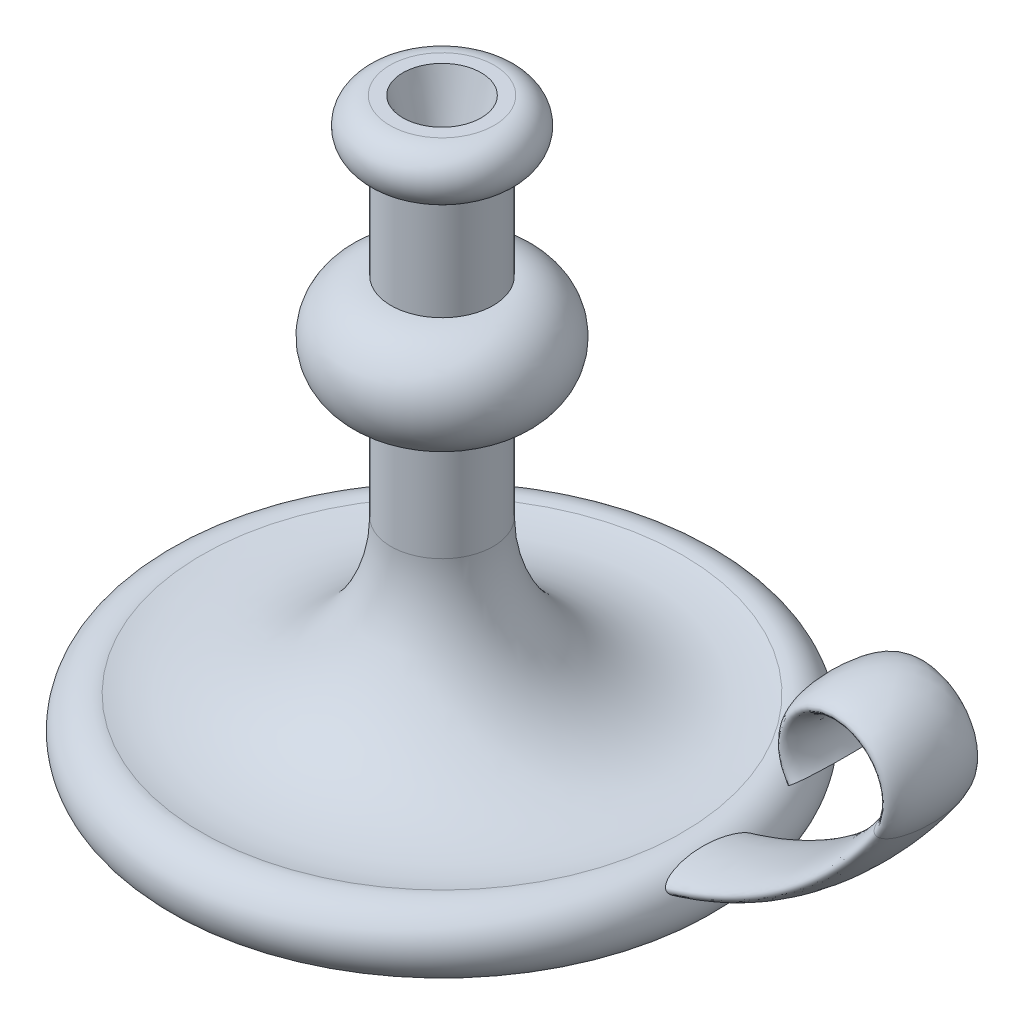
SolidWorks part; units mm, degrees
ref_plane "Front" through (0, 0, 0) normal (0, 0, 1) x (1, 0, 0)
ref_plane "Top" through (0, 0, 0) normal (0, 1, 0) x (1, 0, 0)
ref_plane "Right" through (0, 0, 0) normal (1, 0, 0) x (0, 0, -1)
sketch "草圖1" plane through (0, 0, 0) normal (0, 0, 1) x (1, 0, 0)
  line L0 (0, 0) -> (0, 220)
  line L1 (0, 220) -> (20, 220)
  line L2 (0, 0) -> (103.3169, 0)
  line L3 (19.5986, 200.0081) -> (19.5986, 160.0081)
  line L4 (19.5986, 120.0081) -> (19.5986, 80.0081)
  arc A0 (20, 220) -> (19.5986, 200.0081) centre (20, 210) cw
  arc A1 (19.5986, 160.0081) -> (19.5986, 120.0081) centre (19.5986, 140.0081) cw
  arc A2 (19.5986, 80.0081) -> (92.1449, 21.3345) centre (79.5986, 80.0081) ccw
  arc A3 (92.1449, 21.3345) -> (103.3169, 0) centre (94.7587, 9.1108) cw
  point P13 (0, 0)
  point P15 (0, 0)
  point P16 (0, 0)
  point P17 (0, 0)
  point P18 (0, 0)
  point P19 (0, 0)
  dimension "D4" = 10
  dimension "D5" = 20
  dimension "D7" = 60
  dimension "D8" = 12.5
  dimension "D1" = 220
  dimension "D2" = 20
  dimension "D3" = 103.3169
  dimension "D6" = 40
revolve "旋轉1" add sketch "草圖1" angle 360 about L0
sketch "草圖2" plane through (0, 0, 0) normal (0, 0, 1) x (1, 0, 0)
  line L0 (0, 10) -> (60, 10)
  line L1 (0, 227.4356) -> (0, 175.1288) construction
  line L2 (0, 200.0081) -> (0, 160.0081) construction
  line L3 (-103.3169, 0) -> (103.3169, 0) construction
  arc A0 (60, 10) -> (183.5921, 75) centre (60, 160) ccw
  arc A1 (183.5921, 75) -> (150.6342, 75) centre (167.1131, 86.3333) ccw
  dimension "D2" = 20
  dimension "D3" = 150
  dimension "D1" = 60
  dimension "D4" = 65
  dimension "D5" = 10
sketch "草圖3" plane through (0, 0, 0) normal (1, 0, 0) x (0, 0, -1)
  ellipse E0 centre (0, 10) end of major axis (17.5, 10) minor radius 5
  dimension "D1" = 35
  dimension "D2" = 10
sweep "掃出1" add profiles "草圖3" path "草圖2"
sketch "草圖5" plane through (0, 220, 0) normal (0, 1, 0) x (1, 0, 0)
  circle A0 centre (0, 0) radius 15
  dimension "D1" = 30
extrude "除料-伸長1" cut sketch "草圖5" against normal blind 25 draft 15
